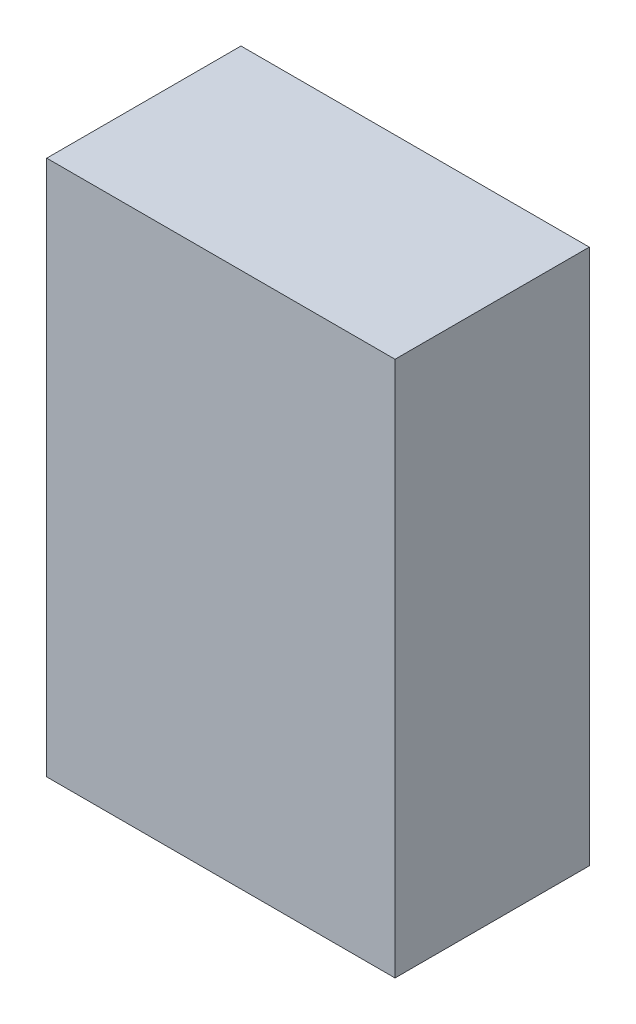
SolidWorks part; units mm, degrees
material "PBT General Purpose"
ref_plane "Front Plane" through (0, 0, 0) normal (0, 0, 1) x (1, 0, 0)
ref_plane "Top Plane" through (0, 0, 0) normal (0, 1, 0) x (1, 0, 0)
ref_plane "Right Plane" through (0, 0, 0) normal (1, 0, 0) x (0, 0, -1)
sketch "Sketch1" plane through (0, 0, 0) normal (0, 1, 0) x (1, 0, 0)
  line L1 (0, 0) -> (660.4, 0)
  line L2 (0, 0) -> (0, 368.3)
  line L3 (0, 368.3) -> (660.4, 368.3)
  line L4 (660.4, 0) -> (660.4, 368.3)
  dimension "D1" = 660.4
  dimension "D2" = 368.3
extrude "Extrude1" add sketch "Sketch1" along normal blind 1016
